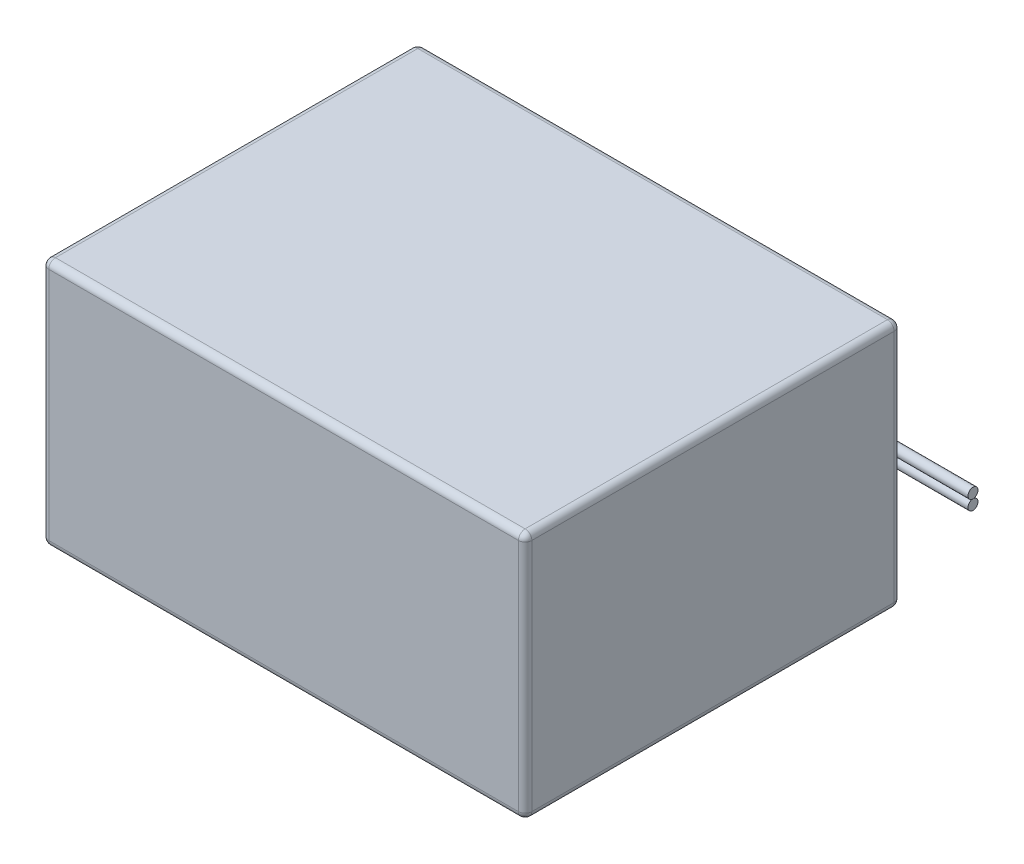
SolidWorks part; units mm, degrees
ref_plane "Front Plane" through (0, 0, 0) normal (0, 0, 1) x (1, 0, 0)
ref_plane "Top Plane" through (0, 0, 0) normal (0, 1, 0) x (1, 0, 0)
ref_plane "Right Plane" through (0, 0, 0) normal (1, 0, 0) x (0, 0, -1)
sketch "Sketch1" plane through (0, 0, 0) normal (0, 1, 0) x (1, 0, 0)
  line L1 (-36, 28) -> (36, 28)
  line L2 (-36, 28) -> (-36, -28)
  line L3 (-36, -28) -> (36, -28)
  line L4 (36, 28) -> (36, -28)
  line L5 (-36, 28) -> (36, -28) construction
  line L6 (-36, -28) -> (36, 28) construction
  point P0 (0, 0)
  dimension "D1" = 56
  dimension "D2" = 72
extrude "Boss-Extrude1" add sketch "Sketch1" along normal blind 37
sketch "Sketch2" plane through (0, 0, 0) normal (1, 0, 0) x (0, 0, -1)
  line L0 (28, 37) -> (28, 0) construction
  line L1 (28, 18.5) -> (38.2156, 18.5) construction
  line L2 (28, 37) -> (28, 0) construction
  circle A0 centre (28.75, 19.25) radius 0.75
  circle A1 centre (28.75, 17.75) radius 0.75
  dimension "D1" = 1.5
extrude "Boss-Extrude2" add sketch "Sketch2" along normal blind 10 and the other way blind 5 from surface at 36 separate body contours A0 | A1 starting at face at (36, 18.5, 0)
fillet "Fillet1" radius 1 12 edges at (36, 18.5, -28) (-36, 18.5, -28) (-36, 18.5, 28) (36, 18.5, 28) (0, 37, 28) (-36, 37, 0) (0, 37, -28) (36, 37, 0) (0, 0, -28) (-36, 0, 0) (0, 0, 28) (36, 0, 0)
